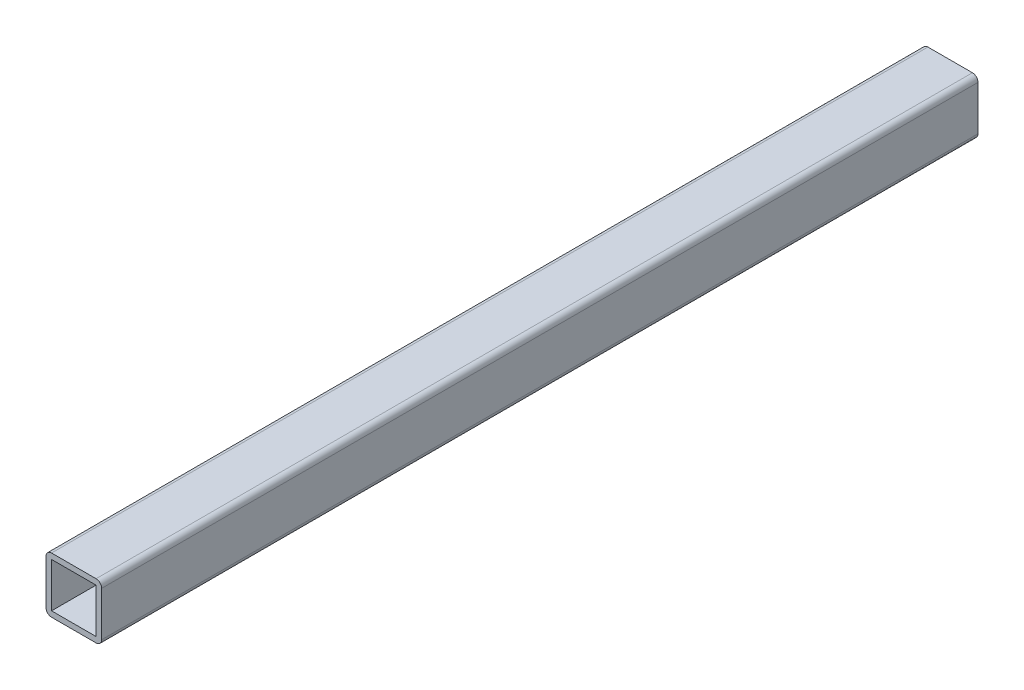
SolidWorks part; units mm, degrees
ref_plane "Front Plane" through (0, 0, 0) normal (0, 0, 1) x (1, 0, 0)
ref_plane "Top Plane" through (0, 0, 0) normal (0, 1, 0) x (1, 0, 0)
ref_plane "Right Plane" through (0, 0, 0) normal (1, 0, 0) x (0, 0, -1)
sketch "Sketch1" plane through (0, 0, 0) normal (0, 0, 1) x (1, 0, 0)
  line L0 (-10.16, 10.16) -> (-10.16, -10.16)
  line L1 (-10.16, 12.7) -> (10.16, 12.7)
  line L2 (-12.7, 10.16) -> (-12.7, -10.16)
  line L3 (-10.16, -12.7) -> (10.16, -12.7)
  line L4 (12.7, 10.16) -> (12.7, -10.16)
  line L5 (-12.7, 12.7) -> (12.7, -12.7) construction
  line L6 (-12.7, -12.7) -> (12.7, 12.7) construction
  line L7 (-10.16, -10.16) -> (10.16, -10.16)
  line L8 (10.16, 10.16) -> (10.16, -10.16)
  line L9 (-10.16, 10.16) -> (10.16, 10.16)
  line L10 (-12.7, 12.7) -> (-12.7, -12.7) construction
  line L11 (-12.7, -12.7) -> (12.7, -12.7) construction
  line L12 (12.7, 12.7) -> (12.7, -12.7) construction
  line L13 (-12.7, 12.7) -> (12.7, 12.7) construction
  arc A0 (-12.7, -10.16) -> (-10.16, -12.7) centre (-10.16, -10.16) ccw
  arc A1 (10.16, -12.7) -> (12.7, -10.16) centre (10.16, -10.16) ccw
  arc A2 (10.16, 12.7) -> (12.7, 10.16) centre (10.16, 10.16) cw
  arc A3 (-12.7, 10.16) -> (-10.16, 12.7) centre (-10.16, 10.16) cw
  point P0 (0, 0)
  dimension "D4" = 2.54
  dimension "D1" = 25.4
  dimension "D2" = 25.4
  dimension "D3" = 2.54
extrude "Boss-Extrude1" add sketch "Sketch1" along normal blind 400 contours L2 A0 L3 A1 L4 A2 L1 A3
